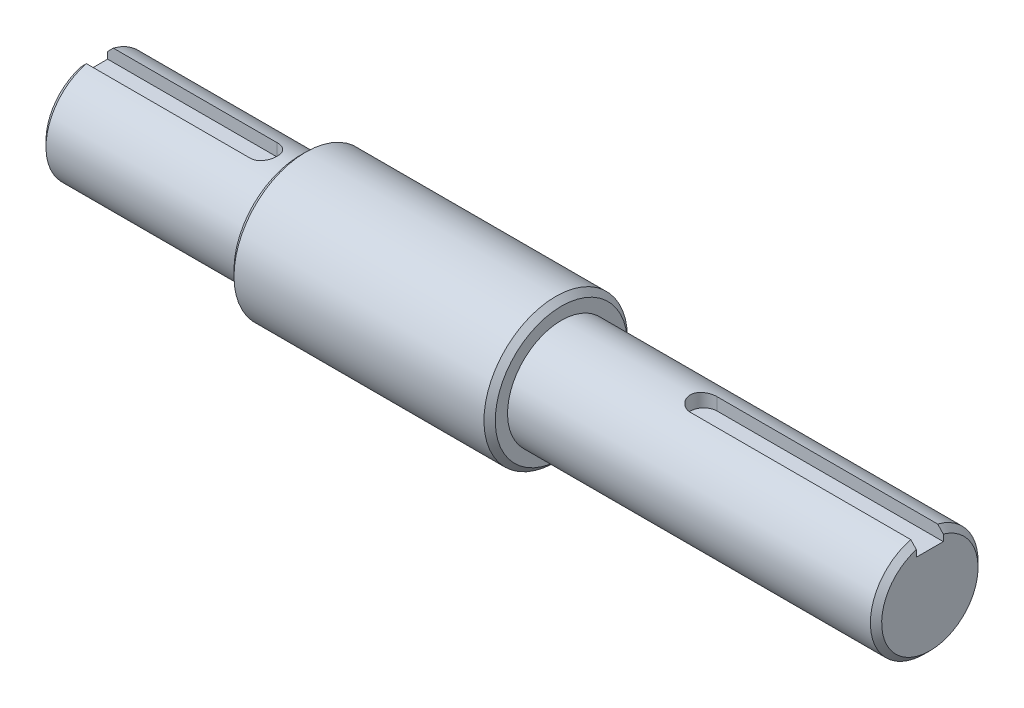
SolidWorks part; units mm, degrees
ref_plane "Alzado" through (0, 0, 0) normal (0, 0, 1) x (1, 0, 0)
ref_plane "Planta" through (0, 0, 0) normal (0, 1, 0) x (1, 0, 0)
ref_plane "Vista lateral" through (0, 0, 0) normal (1, 0, 0) x (0, 0, -1)
sketch "Croquis1" plane through (0, 0, 0) normal (0, 0, 1) x (1, 0, 0)
  line L0 (-23.1144, 0) -> (23.1144, 0)
  line L1 (23.1144, 0) -> (23.1144, -3.175)
  line L2 (23.1144, -3.175) -> (88.3114, -3.175)
  line L3 (88.3114, -3.175) -> (88.3114, -12.7)
  line L4 (88.3114, -12.7) -> (-59.5578, -12.7) construction
  line L5 (-59.5578, -12.7) -> (-59.5578, -3.175)
  line L6 (-59.5578, -3.175) -> (-23.1144, -3.175)
  line L7 (-23.1144, -3.175) -> (-23.1144, 0)
  line L8 (88.3114, -12.7) -> (-59.5578, -12.7)
  dimension "D1" = 25.4
  dimension "D2" = 19.05
  dimension "D3" = 65.1971
  dimension "D4" = 46.2287
  dimension "D5" = 36.4435
revolve "Revolución1" add sketch "Croquis1" angle 360 about L4
ref_plane "Plano1" through (0, -3.175, 0) normal (0, 1, 0) x (1, 0, 0)
sketch "Croquis2" plane through (0, -3.175, 0) normal (0, 1, 0) x (1, 0, 0)
  line L0 (48.3114, 0) -> (88.3114, 0) construction
  line L1 (48.3114, 2.3813) -> (88.3114, 2.3813)
  line L2 (48.3114, -2.3813) -> (88.3114, -2.3813)
  line L3 (88.3114, -9.525) -> (88.3114, 9.525) construction
  line L4 (-59.5578, 0) -> (-29.5578, 0) construction
  line L5 (-59.5578, 9.525) -> (-59.5578, -9.525) construction
  line L6 (-59.5578, 2.3813) -> (-29.5578, 2.3813)
  line L7 (-59.5578, -2.3813) -> (-29.5578, -2.3813)
  arc A0 (48.3114, 2.3813) -> (48.3114, -2.3813) centre (48.3114, 0) ccw
  arc A1 (88.3114, -2.3813) -> (88.3114, 2.3813) centre (88.3114, 0) ccw
  arc A2 (-59.5578, 2.3813) -> (-59.5578, -2.3813) centre (-59.5578, 0) ccw
  arc A3 (-29.5578, -2.3813) -> (-29.5578, 2.3813) centre (-29.5578, 0) ccw
  point P3 (68.3114, 0)
  point P14 (-44.5578, 0)
  dimension "D1" = 4.7625
  dimension "D2" = 40
  dimension "D3" = 4.7625
  dimension "D4" = 30
extrude "Cortar-Extruir1" cut sketch "Croquis2" against normal blind 2.5 contours L1 A1 L2 A0 | L7 A3 L6 A2
chamfer "Chaflán1" distance 1 angle 45 4 edges at (-59.5578, -22.225, 0) (88.3114, -22.225, 0) (23.1144, 0, 0) (-23.1144, 0, 0)
